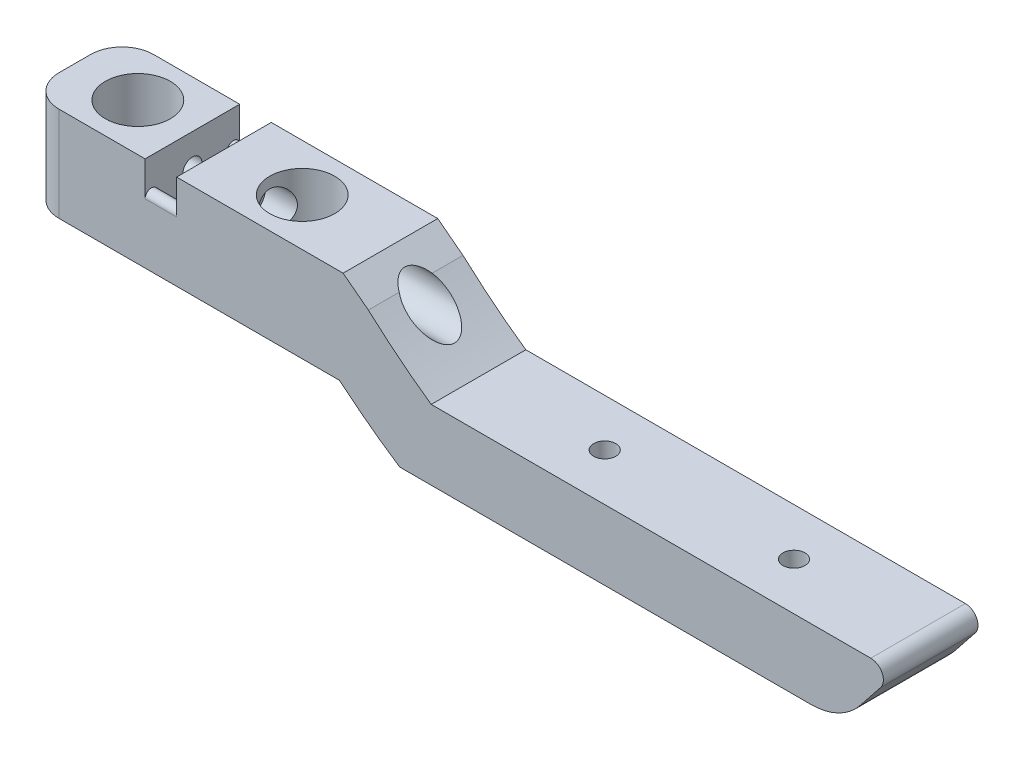
SolidWorks part; units mm, degrees
material "Vero PureWhite"
ref_plane "前视基准面" through (0, 0, 0) normal (0, 0, 1) x (1, 0, 0)
ref_plane "上视基准面" through (0, 0, 0) normal (0, 1, 0) x (1, 0, 0)
ref_plane "右视基准面" through (0, 0, 0) normal (1, 0, 0) x (0, 0, -1)
sketch "草图1" plane through (0, 0, 0) normal (0, 0, 1) x (1, 0, 0)
  line L0 (40, 0) -> (128, 0) construction
  line L1 (-40, 7.5) -> (40, 7.5)
  line L2 (-40, 7.5) -> (-40, -7.5)
  line L3 (-40, -7.5) -> (40, -7.5)
  line L4 (40, 7.5) -> (40, -7.5) construction
  line L5 (-40, 7.5) -> (40, -7.5) construction
  line L6 (-40, -7.5) -> (40, 7.5) construction
  line L7 (40, 7.5) -> (44.036, 4.4396)
  line L8 (123.964, 4.4396) -> (132.036, -4.4396)
  spline S0 degree 2 poles (40, 0) (84, -40) (128, 0) knots 0 0 0 1 1 1 construction
  spline S1 degree 1 poles (35.964, -4.4396) (132.036, -4.4396) knots 0 0 1 1 construction
  spline S2 degree 2 poles (35.964, -4.4396) (44.6171, -12.3274) (59.4834, -20.7889) (71.6465, -24.9443) (84, -26.3519) (96.3535, -24.9443) (108.5166, -20.7889) (123.3829, -12.3274) (132.036, -4.4396) knots 0 0 0 0.1875 0.3125 0.4375 0.5625 0.6875 0.8125 1 1 1
  spline S3 degree 1 poles (44.036, 4.4396) (123.964, 4.4396) knots 0 0 1 1 construction
  spline S4 degree 2 poles (44.036, 4.4396) (51.8829, -2.6726) (64.5166, -9.8361) (74.3535, -13.1807) (84, -14.2731) (93.6465, -13.1807) (103.4834, -9.8361) (116.1171, -2.6726) (123.964, 4.4396) knots 0 0 0 0.1875 0.3125 0.4375 0.5625 0.6875 0.8125 1 1 1
  point P0 (0, 0)
  point P8 (84, 0)
  dimension "D1" = 80
  dimension "D2" = 15
  dimension "D3" = 20
  dimension "D4" = 88
  dimension "D5" = 6
  dimension "D6" = 6
extrude "凸台-拉伸1" add sketch "草图1" along normal blind 15
sketch "草图2" plane through (0, 7.5, 0) normal (0, 1, 0) x (1, 0, 0)
  line L0 (-40, -15) -> (-40, 0) construction
  circle A0 centre (0, -7.5) radius 5.15
  point P4 (-40, -7.5)
  dimension "D1" = 10.3
extrude "切除-拉伸1" cut sketch "草图2" against normal blind 15
sketch "草图4" plane through (0, 0, 0) normal (0, 0, -1) x (-1, 0, 0)
  line L0 (-40, 7.5) -> (-44.036, 7.5)
  line L1 (-44.036, 7.5) -> (-44.036, 4.4396)
  line L2 (-40, 7.5) -> (-44.036, 4.4396) construction
  line L3 (-40, 7.5) -> (-44.036, 4.4396)
extrude "凸台-拉伸3" add sketch "草图4" against normal up to surface (15 mm away) up to face at (30.4628, 0.4156, 15)
sketch "草图5" plane through (0, 0, 0) normal (0, 0, -1) x (-1, 0, 0)
  line L0 (40, 7.5) -> (-44.036, 7.5) construction
  line L1 (-14.15, 7.5) -> (-9.15, 7.5)
  line L2 (-14.15, 7.5) -> (-14.15, -2.5)
  line L3 (-14.15, -2.5) -> (-9.15, -2.5)
  line L4 (-9.15, 7.5) -> (-9.15, -2.5)
  line L5 (-5.15, 7.5) -> (-5.15, -7.5) construction
  dimension "D1" = 10
  dimension "D2" = 5
  dimension "D3" = 4
extrude "切除-拉伸3" cut sketch "草图5" against normal blind 15
sketch "草图6" plane through (44.036, 0, 0) normal (1, 0, 0) x (0, 0, -1)
  line L0 (-15, 7.5) -> (0, 7.5) construction
  circle A0 centre (-7.5, 2.5) radius 3.25
  point P4 (-7.5, 7.5)
  dimension "D2" = 6.5
  dimension "D1" = 5
extrude "切除-拉伸4" cut sketch "草图6" against normal blind 27 and the other way blind 15
sketch "草图7" plane through (9.15, 0, 0) normal (1, 0, 0) x (0, 0, -1)
  circle A0 centre (-7.5, 2.5) radius 1.5
  dimension "D1" = 3
extrude "切除-拉伸5" cut sketch "草图7" against normal blind 3.5
sketch "草图9" plane through (0, 0, 0) normal (0, 0, -1) x (-1, 0, 0)
  line L0 (-49, -14.6289) -> (-119, -14.6289)
  spline S0 degree 2 poles (225.0033, 1968.336) (167.9844, 108.6805) (-59.4834, -20.7889) (-71.6465, -24.9443) (-84, -26.3519) (-96.3535, -24.9443) (-108.5166, -20.7889) (-336.208, 108.8077) (-393.1182, 1972.091) knots -4.46901 -4.46901 -4.46901 0.1875 0.3125 0.4375 0.5625 0.6875 0.8125 5.473709 5.473709 5.473709 only from (-39.4569, -7.5) to (-132.036, -4.4396) construction
  spline S1 degree 2 poles (-49, -14.6289) (-51.2598, -16.1082) (-59.4834, -20.7889) (-71.6465, -24.9443) (-84, -26.3519) (-96.3535, -24.9443) (-108.5166, -20.7889) (-116.7402, -16.1082) (-119, -14.6289) knots 0.139633 0.139633 0.139633 0.1875 0.3125 0.4375 0.5625 0.6875 0.8125 0.860367 0.860367 0.860367
  dimension "D1" = 70
extrude "切除-拉伸7" cut sketch "草图9" against normal up to surface (15 mm away) up to face at (23.9887, 1.1736, 15)
sketch "草图10" plane through (0, 0, 0) normal (0, 0, -1) x (-1, 0, 0)
  line L0 (-114, -3.5316) -> (-54, -3.5316)
  spline S0 degree 2 poles (479.3937, 1931.0185) (128.2147, 99.4447) (-64.5166, -9.8361) (-74.3535, -13.1807) (-84, -14.2731) (-93.6465, -13.1807) (-103.4834, -9.8361) (-296.214, 99.4443) (-647.3911, 1931.0053) knots -4.454817 -4.454817 -4.454817 0.1875 0.3125 0.4375 0.5625 0.6875 0.8125 5.454801 5.454801 5.454801 only from (-44.036, 4.4396) to (-123.964, 4.4396) construction
  spline S1 degree 2 poles (-54, -3.5316) (-56.7487, -5.4316) (-64.5166, -9.8361) (-74.3535, -13.1807) (-84, -14.2731) (-93.6465, -13.1807) (-103.4834, -9.8361) (-111.2513, -5.4316) (-114, -3.5316) knots 0.120356 0.120356 0.120356 0.1875 0.3125 0.4375 0.5625 0.6875 0.8125 0.879644 0.879644 0.879644
  dimension "D1" = 60
extrude "凸台-拉伸4" add sketch "草图10" against normal up to surface (15 mm away) up to face at (35.9135, -1.2576, 15)
sketch "草图12" plane through (0, -3.5316, 0) normal (0, 1, 0) x (1, 0, 0)
  line L0 (119, -15) -> (119, 0) construction
  line L1 (54, -15) -> (54, 0) construction
  circle A0 centre (74, -7.5) radius 1.75
  circle A1 centre (104, -7.5) radius 1.75
  point P6 (119, -7.5)
  dimension "D2" = 3.5
  dimension "D1" = 30
  dimension "D3" = 20
extrude "切除-拉伸9" cut sketch "草图12" against normal blind 50
sketch "草图13" plane through (0, -14.6289, 0) normal (0, -1, 0) x (1, 0, 0)
  line L1 (75.6743, 4.6) -> (77.3486, 7.5)
  line L2 (77.3486, 7.5) -> (75.6743, 10.4)
  line L3 (75.6743, 10.4) -> (72.3257, 10.4)
  line L4 (72.3257, 10.4) -> (70.6514, 7.5)
  line L5 (70.6514, 7.5) -> (72.3257, 4.6)
  line L6 (72.3257, 4.6) -> (75.6743, 4.6)
  line L7 (105.6743, 4.6) -> (107.3486, 7.5)
  line L8 (107.3486, 7.5) -> (105.6743, 10.4)
  line L9 (105.6743, 10.4) -> (102.3257, 10.4)
  line L10 (102.3257, 10.4) -> (100.6514, 7.5)
  line L11 (100.6514, 7.5) -> (102.3257, 4.6)
  line L12 (102.3257, 4.6) -> (105.6743, 4.6)
  circle A0 centre (74, 7.5) radius 2.9 construction
  circle A1 centre (104, 7.5) radius 2.9 construction
  dimension "D1" = 5.8
extrude "切除-拉伸10" cut sketch "草图13" against normal blind 3
sketch "草图14" plane through (17.036, 0, 0) normal (1, 0, 0) x (0, 0, -1)
  circle A1 centre (-7.5, 2.5) radius 1.65
  dimension "D1" = 3.3
extrude "切除-拉伸11" cut sketch "草图14" against normal blind 5
sketch "草图15" plane through (0, 7.5, 0) normal (0, 1, 0) x (1, 0, 0)
  line L0 (14.15, -15) -> (14.15, 0) construction
  line L1 (17.036, -7.5) -> (20.9, -7.5) construction
  line L2 (17.036, -10.75) -> (17.036, -4.25) construction
  line L3 (0, -7.5) -> (26.05, -7.5) construction
  circle A0 centre (26.05, -7.5) radius 5.15
  circle A1 centre (0, -7.5) radius 5.15 construction
  circle A2 centre (0, -7.5) radius 5.15 construction
  point P6 (14.15, -7.5)
  dimension "D1" = 11.9
extrude "切除-拉伸12" cut sketch "草图15" against normal blind 15
sketch "草图16" plane through (0, 0, 0) normal (0, 0, -1) x (-1, 0, 0)
  line L0 (-44.036, 4.4396) -> (-40.036, 7.5)
  line L1 (-14.15, 7.5) -> (-44.036, 7.5) construction
  line L2 (-40.036, 7.5) -> (-44.036, 7.5)
  line L3 (-44.036, 7.5) -> (-44.036, 4.4396)
  dimension "D1" = 4
extrude "切除-拉伸13" cut sketch "草图16" against normal blind 15
sketch "草图17" plane through (0, 0, 0) normal (0, 0, -1) x (-1, 0, 0)
  line L0 (-114, -3.5316) -> (-155.4509, -3.5316)
  line L1 (-155.4509, -3.5316) -> (-96.9867, 29.7083)
  line L2 (-96.9867, 29.7083) -> (-114, -3.5316)
extrude "切除-拉伸14" cut sketch "草图17" against normal blind 15
sketch "草图18" plane through (0, 0, 0) normal (0, 0, -1) x (-1, 0, 0)
  line L0 (40, 7.5) -> (-9.15, 7.5) construction
  line L1 (10, 7.5) -> (40, 7.5)
  line L2 (10, 7.5) -> (10, -7.5)
  line L3 (10, -7.5) -> (40, -7.5)
  line L4 (40, 7.5) -> (40, -7.5)
  dimension "D1" = 30
extrude "切除-拉伸15" cut sketch "草图18" against normal blind 15
sketch "草图19" plane through (0, 0, 15) normal (0, 0, 1) x (1, 0, 0)
  line L0 (119, -14.6289) -> (127.8151, -3.5316)
  line L1 (54, -3.5316) -> (131.2105, -3.5316) construction
  line L2 (127.8151, -3.5316) -> (136.0521, -3.5316)
  line L3 (136.0521, -3.5316) -> (119, -14.6289)
extrude "切除-拉伸16" cut sketch "草图19" against normal blind 135
fillet "圆角3" radius 10 1 edges at (119, -14.6289, 7.5)
fillet "圆角4" radius 2 1 edges at (127.8151, -3.5316, 7.5)
fillet "圆角5" radius 5 2 edges at (-10, 0, 0) (-10, 0, 15)
sketch "草图20" plane through (9.15, 0, 0) normal (1, 0, 0) x (0, 0, -1)
  line L0 (-10, -2.5) -> (-15, -2.5)
  line L1 (-15, -2.5) -> (0, -2.5) construction
  line L2 (-15, -2.5) -> (-15, 5.5)
  line L3 (-15, -2.5) -> (-15, 7.5) construction
  line L4 (-15, 5.5) -> (-10, -2.5)
  line L5 (-7.5, -2.5) -> (-7.5, -0.6948) construction
  line L6 (0, 5.5) -> (-5, -2.5)
  line L7 (0, -2.5) -> (0, 5.5)
  line L8 (-5, -2.5) -> (0, -2.5)
  dimension "D1" = 5
  dimension "D2" = 8
extrude "凸台-拉伸5" add sketch "草图20" along normal up to surface (5 mm away) up to face at (14.15, 4.15, 7.5)
fillet "圆角6" radius 1 2 edges at (11.65, 5.5, 15) (11.65, 5.5, 0)
sketch "草图21" plane through (9.15, 0, 0) normal (1, 0, 0) x (0, 0, -1)
  line L6 (-5, -2.5) -> (-1.848, 2.5432)
  line L7 (0, 2.0132) -> (0, 7.5)
  line L8 (0, 7.5) -> (-15, 7.5)
  line L9 (-15, 7.5) -> (-15, 2.0132)
  line L10 (-13.152, 2.5432) -> (-10, -2.5)
  line L11 (-10, -2.5) -> (-5, -2.5)
  line L12 (-5, -2.5) -> (-1.848, 2.5432)
  line L13 (0, 2.0132) -> (0, 7.5)
  line L14 (0, 7.5) -> (-15, 7.5)
  line L15 (-15, 7.5) -> (-15, 2.0132)
  line L16 (-13.152, 2.5432) -> (-10, -2.5)
  line L17 (-10, -2.5) -> (-5, -2.5)
  arc A2 (0, 2.0132) -> (-1.848, 2.5432) centre (-1, 2.0132) ccw
  arc A3 (-13.152, 2.5432) -> (-15, 2.0132) centre (-14, 2.0132) ccw
  arc A4 (0, 2.0132) -> (-1.848, 2.5432) centre (-1, 2.0132) ccw
  arc A5 (-13.152, 2.5432) -> (-15, 2.0132) centre (-14, 2.0132) ccw
  dimension "D1" = 0
extrude "切除-拉伸17" cut sketch "草图21" against normal blind 0.5
sketch "草图22" plane through (14.15, 0, 0) normal (-1, 0, 0) x (0, 0, 1)
  line L6 (0, 7.5) -> (0, 2.0132)
  line L7 (1.848, 2.5432) -> (5, -2.5)
  line L8 (5, -2.5) -> (10, -2.5)
  line L9 (10, -2.5) -> (13.152, 2.5432)
  line L10 (15, 2.0132) -> (15, 7.5)
  line L11 (15, 7.5) -> (0, 7.5)
  line L12 (0, 7.5) -> (0, 2.0132)
  line L13 (1.848, 2.5432) -> (5, -2.5)
  line L14 (5, -2.5) -> (10, -2.5)
  line L15 (10, -2.5) -> (13.152, 2.5432)
  line L16 (15, 2.0132) -> (15, 7.5)
  line L17 (15, 7.5) -> (0, 7.5)
  circle A0 centre (7.5, 2.5) radius 1.65 construction
  circle A1 centre (7.5, 2.5) radius 1.65
  arc A2 (1.848, 2.5432) -> (0, 2.0132) centre (1, 2.0132) ccw
  arc A3 (15, 2.0132) -> (13.152, 2.5432) centre (14, 2.0132) ccw
  arc A4 (1.848, 2.5432) -> (0, 2.0132) centre (1, 2.0132) ccw
  arc A5 (15, 2.0132) -> (13.152, 2.5432) centre (14, 2.0132) ccw
  dimension "D1" = 0
extrude "凸台-拉伸6" add sketch "草图22" along normal blind 0.5
scale "缩放比例1" scale about origin uniform scaling yes scale factor 0.6
